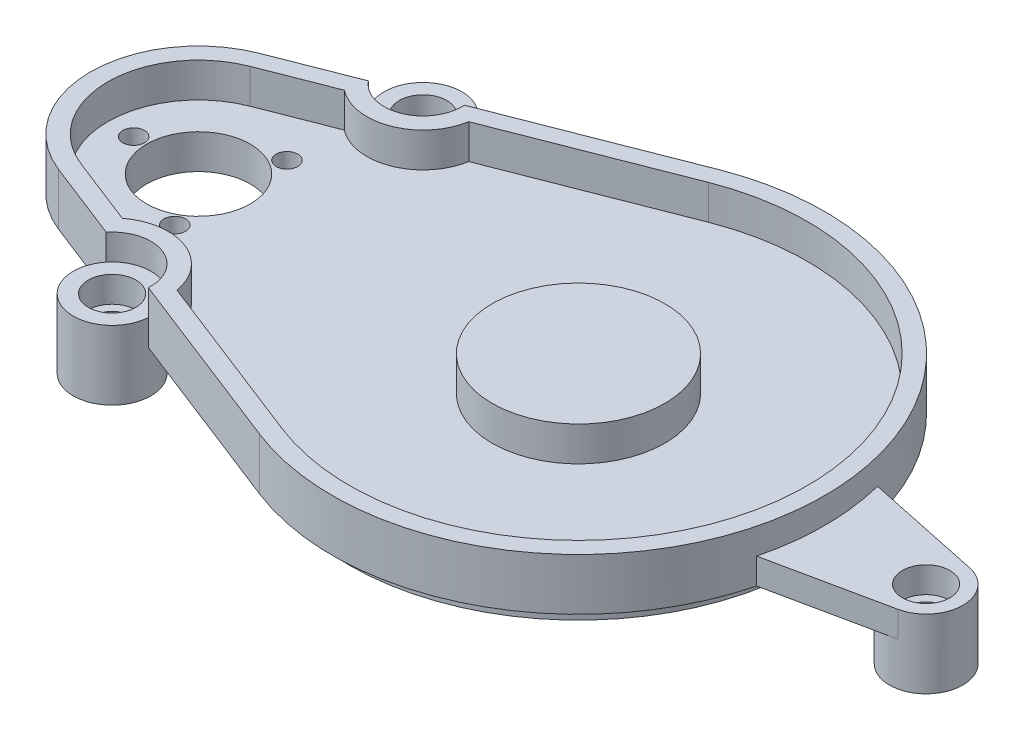
SolidWorks part; units mm, degrees
ref_plane "Front Plane" through (0, 0, 0) normal (0, 0, 1) x (1, 0, 0)
ref_plane "Top Plane" through (0, 0, 0) normal (0, 1, 0) x (1, 0, 0)
ref_plane "Right Plane" through (0, 0, 0) normal (1, 0, 0) x (0, 0, -1)
sketch "Sketch1" plane through (0, 0, 0) normal (0, 1, 0) x (1, 0, 0)
  line L0 (-22, 0) -> (22, 0) construction
  line L1 (-26.5455, 11.6443) -> (11.6364, 26.5489)
  line L2 (-26.5455, -11.6443) -> (11.6364, -26.5489)
  line L3 (-14, 18) -> (-14, -18) construction
  circle A0 centre (22, 0) radius 28.5
  circle A1 centre (-22, 0) radius 12.5
  circle A7 centre (-14, -18) radius 4.5
  circle A8 centre (-14, -18) radius 4.5 construction
  circle A9 centre (-14, 18) radius 4.5 construction
  circle A10 centre (-14, 18) radius 4.5
  point P4 (0, 0)
  point P19 (-14, 0)
  point P27 (-22, 0)
  dimension "D1" = 57
  dimension "D2" = 25
  dimension "D4" = 8
  dimension "D5" = 9
  dimension "D7" = 9
  dimension "D3" = 44
  dimension "D6" = 36
extrude "Boss-Extrude1" add sketch "Sketch1" along normal blind 6 contours A1 | L1 A10 A1 L2 A7 A0 | A0 L2
shell "Shell1" thickness 2
sketch "Sketch2" plane through (0, 0, 0) normal (0, -1, 0) x (1, 0, 0)
  line L0 (63.1254, 4.1589) -> (49.627, 7)
  line L1 (62.25, 0) -> (0, 0) construction
  line L2 (49.627, 7) -> (49.627, -7) construction
  line L3 (63.1254, -4.1589) -> (49.627, -7)
  circle A0 centre (62.25, 0) radius 4.25
  arc A1 (11.6364, -26.5489) -> (11.6364, 26.5489) centre (22, 0) ccw construction
  circle A2 centre (22, 0) radius 28.5
  circle A3 centre (62.25, 0) radius 2.75
  circle A4 centre (-14, -18) radius 4.5
  circle A5 centre (-14, -18) radius 2.75
  circle A6 centre (-14, 18) radius 2.75
  circle A7 centre (-14, 18) radius 4.5
  point P7 (49.627, 0)
  arc M8 (11.6364, -26.5489) -> (11.6364, 26.5489) centre (22, 0) ccw
  dimension "D1" = 40.25
  dimension "D2" = 8.5
  dimension "D4" = 57
  dimension "D5" = 5.5
  dimension "D6" = 9
  dimension "D7" = 5.5
  dimension "D8" = 36
  dimension "D3" = 14
extrude "Boss-Extrude2" add sketch "Sketch2" against normal blind 3 separate body contours A0 L0 L3 M8 | A0 A3 | A4 | A7 | A5 | A6
sketch "Sketch3" plane through (0, 0, 0) normal (0, -1, 0) x (1, 0, 0)
  line L0 (-34.5, 0) -> (50.5, 0) construction
  circle A0 centre (-14, 18) radius 4.5 construction
  circle A1 centre (-14, 18) radius 4.5
  arc A2 (-26.5455, 11.6443) -> (-26.5455, -11.6443) centre (-22, 0) ccw construction
  arc A3 (49.627, -7) -> (49.627, 7) centre (22, 0) ccw construction
  circle A5 centre (62.25, 0) radius 4.25
  circle A6 centre (-14, -18) radius 4.5 construction
  circle A7 centre (-14, -18) radius 4.5
  dimension "D1" = 8.5
extrude "Boss-Extrude3" add sketch "Sketch3" along normal blind 5
sketch "Sketch4" plane through (0, -5, 0) normal (0, -1, 0) x (1, 0, 0)
  line L0 (0, 0) -> (62.25, 0) construction
  circle A0 centre (-14, 18) radius 3.25
  circle A1 centre (-14, -18) radius 3.25
  circle A2 centre (62.25, 0) radius 3.25
  dimension "D1" = 6.5
  dimension "D2" = 6.5
extrude "Cut-Extrude1" cut sketch "Sketch4" against normal blind 2
sketch "Sketch5" plane through (0, -3, 0) normal (0, -1, 0) x (1, 0, 0)
  line L0 (0, 0) -> (62.25, 0) construction
  circle A0 centre (-14, 18) radius 1.75
  circle A1 centre (-14, -18) radius 1.75
  circle A2 centre (62.25, 0) radius 1.75
  dimension "D1" = 3.5
  dimension "D2" = 3.5
extrude "Cut-Extrude2" cut sketch "Sketch5" against normal through all
sketch "Sketch7" plane through (0, 0, 0) normal (0, -1, 0) x (1, 0, 0)
  line L0 (1.0634, 22.4216) -> (1.0634, -22.4216)
  line L1 (-9.5096, 18.2944) -> (11.6364, 26.5489) construction
  line L2 (-9.5096, -18.2944) -> (11.6364, -26.5489) construction
  circle A0 centre (-22, 0) radius 11
  circle A2 centre (22, 0) radius 26.5
  dimension "D1" = 22
  dimension "D2" = 53
extrude "Boss-Extrude5" add sketch "Sketch7" along normal blind 2 contours A0 | L0 A2
sketch "Sketch6" plane through (0, 2, 0) normal (0, 1, 0) x (1, 0, 0)
  circle A0 centre (-22, 0) radius 7.5 construction
  circle A2 centre (-29.5, 0) radius 1.25
  circle A3 centre (-18.25, 6.4952) radius 1.25
  circle A4 centre (-18.25, -6.4952) radius 1.25
  circle A5 centre (-22, 0) radius 6
  point P11 (-22, 0)
  dimension "D1" = 15
  dimension "D2" = 2.5
  dimension "D4" = 12
  dimension "D3" = 3
extrude "Cut-Extrude4" cut sketch "Sketch6" against normal through all
sketch "Sketch9" plane through (0, 2, 0) normal (0, 1, 0) x (1, 0, 0)
  circle A0 centre (22, 0) radius 10
  dimension "D1" = 20
extrude "Boss-Extrude6" add sketch "Sketch9" along normal up to surface (4 mm away) up to face at (-5.7856, 6, 0)
